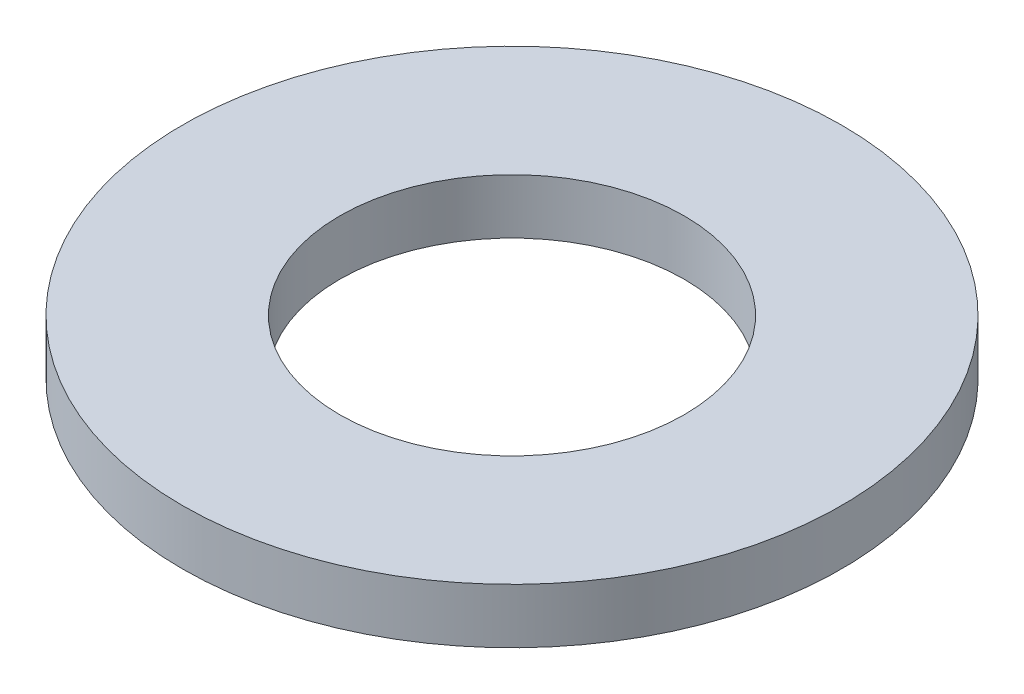
SolidWorks part; units mm, degrees
material "PET"
ref_plane "Front Plane" through (0, 0, 0) normal (0, 0, 1) x (1, 0, 0)
ref_plane "Top Plane" through (0, 0, 0) normal (0, 1, 0) x (1, 0, 0)
ref_plane "Right Plane" through (0, 0, 0) normal (1, 0, 0) x (0, 0, -1)
sketch "Sketch1" plane through (0, 0, 0) normal (0, 1, 0) x (1, 0, 0)
  circle A0 centre (0, 0) radius 2.4892
  circle A1 centre (0, 0) radius 4.7625
  dimension "D1" = 4.9784
  dimension "D2" = 9.525
extrude "Boss-Extrude1" add sketch "Sketch1" along normal blind 0.7937
